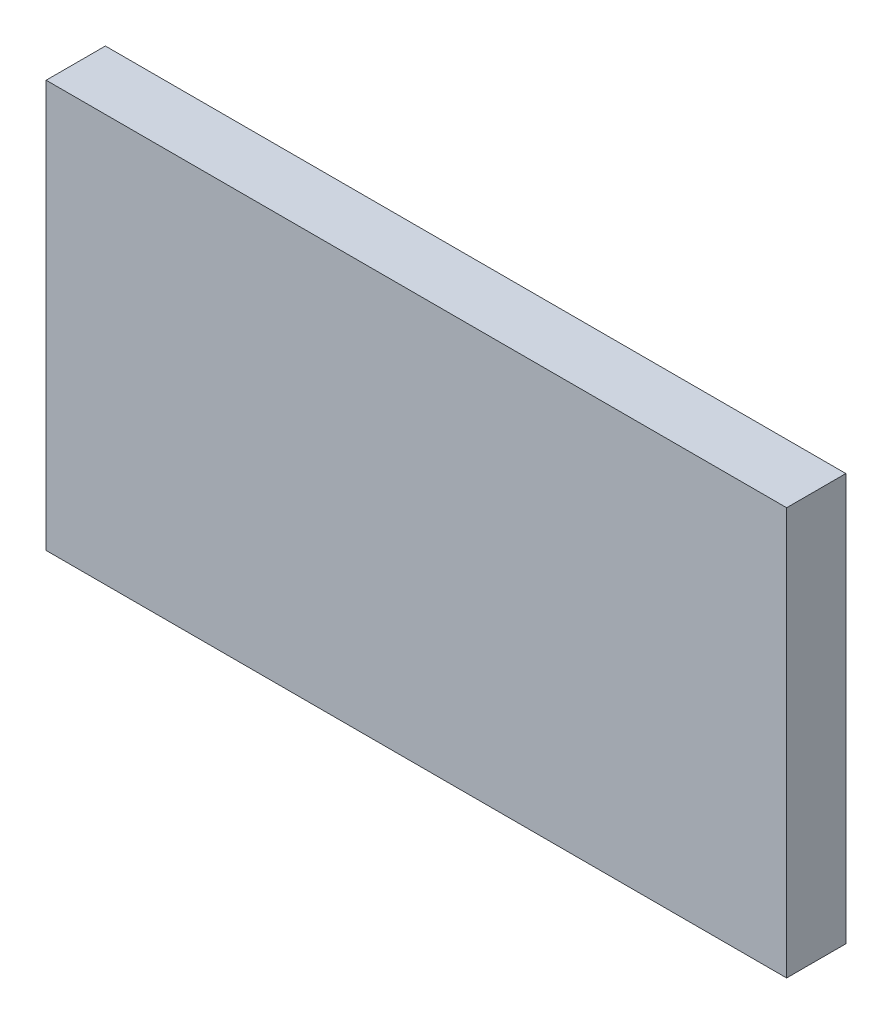
SolidWorks part; units mm, degrees
ref_plane "Front Plane" through (0, 0, 0) normal (0, 0, 1) x (1, 0, 0)
ref_plane "Top Plane" through (0, 0, 0) normal (0, 1, 0) x (1, 0, 0)
ref_plane "Right Plane" through (0, 0, 0) normal (1, 0, 0) x (0, 0, -1)
sketch "Sketch2" plane through (0, 0, 0) normal (0, 0, 1) x (1, 0, 0)
  line L1 (-50, 27.5) -> (50, 27.5)
  line L2 (-50, 27.5) -> (-50, -27.5)
  line L3 (-50, -27.5) -> (50, -27.5)
  line L4 (50, 27.5) -> (50, -27.5)
  line L5 (-50, 27.5) -> (50, -27.5) construction
  line L6 (-50, -27.5) -> (50, 27.5) construction
  point P0 (0, 0)
  dimension "D1" = 55
  dimension "D2" = 100
extrude "Boss-Extrude1" add sketch "Sketch2" along normal blind 8
